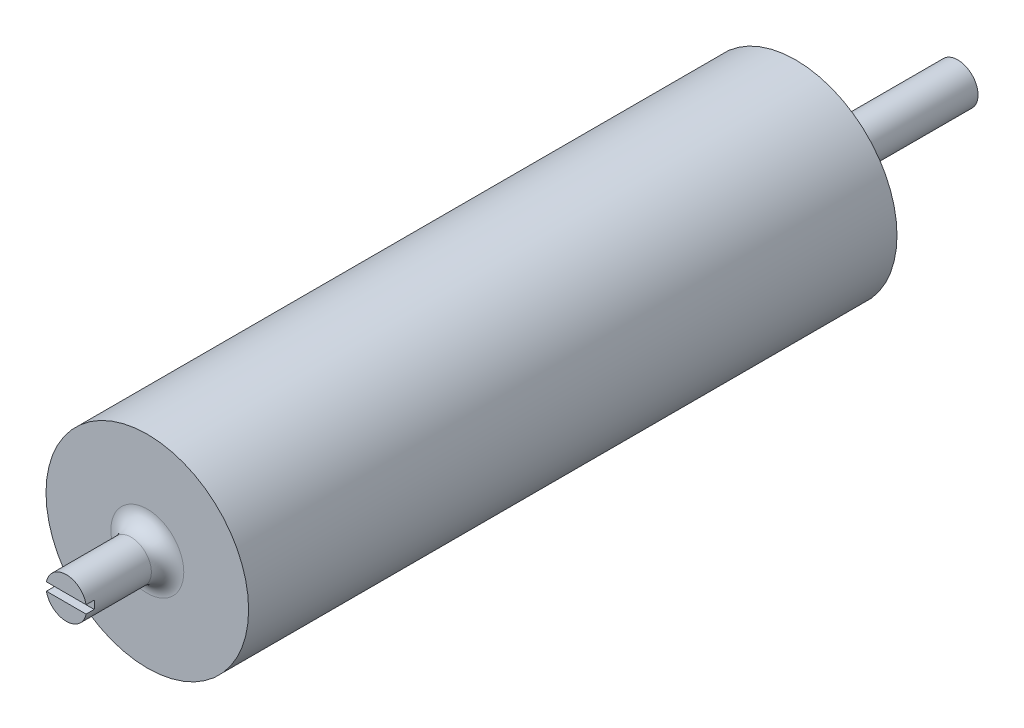
SolidWorks part; units mm, degrees
ref_plane "Plan de face" through (0, 0, 0) normal (0, 0, 1) x (1, 0, 0)
ref_plane "Plan de dessus" through (0, 0, 0) normal (0, 1, 0) x (1, 0, 0)
ref_plane "Plan de droite" through (0, 0, 0) normal (1, 0, 0) x (0, 0, -1)
sketch "Esquisse1" plane through (0, 0, 0) normal (0, 0, 1) x (1, 0, 0)
  circle A0 centre (0, 0) radius 12.5
  dimension "D1" = 25
extrude "Boss.-Extru.1" add sketch "Esquisse1" along normal blind 80
sketch "Esquisse2" plane through (0, 0, 0) normal (0, 0, 1) x (1, 0, 0)
  circle A0 centre (0, 0) radius 2.5
  dimension "D1" = 5
extrude "Boss.-Extru.2" add sketch "Esquisse2" against normal blind 20 and the other way blind 90
fillet "Congé1" radius 2 1 edges at (2.5, 0, 80)
fillet "Congé2" radius 2 1 edges at (2.5, 0, 0)
sketch "Esquisse3" plane through (0, 0, 90) normal (0, 0, 1) x (1, 0, 0)
  circle A0 centre (0, 0) radius 0.5
  dimension "D1" = 1
extrude "Enlèv. mat.-Extru.1" cut sketch "Esquisse3" against normal blind 90 from offset 5 offset against normal yes
sketch "Esquisse5" plane through (0, 0, 90) normal (0, 0, 1) x (1, 0, 0)
  line L0 (-2.5, 0) -> (2.5, 0) construction
  line L1 (-2.4495, -0.5) -> (2.4495, -0.5)
  line L2 (-2.4495, 0.5) -> (2.4495, 0.5)
  arc A0 (2.4495, -0.5) -> (2.4495, 0.5) centre (0, 0) ccw
  circle A1 centre (0, 0) radius 2.5
  arc A2 (-2.4495, 0.5) -> (-2.4495, -0.5) centre (0, 0) ccw
  point P5 (0, 0)
  dimension "D2" = 0.5
  dimension "D1" = 0
extrude "Enlèv. mat.-Extru.3" cut sketch "Esquisse5" against normal blind 1
